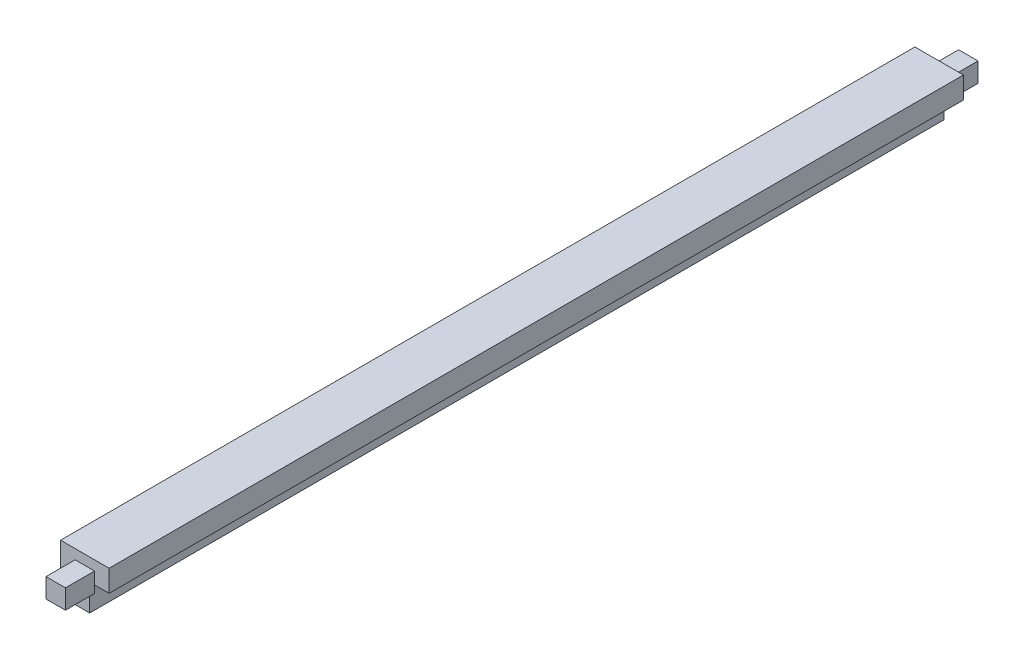
SolidWorks part; units mm, degrees
ref_plane "Front Plane" through (0, 0, 0) normal (0, 0, 1) x (1, 0, 0)
ref_plane "Top Plane" through (0, 0, 0) normal (0, 1, 0) x (1, 0, 0)
ref_plane "Right Plane" through (0, 0, 0) normal (1, 0, 0) x (0, 0, -1)
sketch "Sketch2" plane through (0, 0, 0) normal (0, 1, 0) x (1, 0, 0)
  line L1 (-38.9449, 32.0723) -> (-33.9449, 32.0723)
  line L2 (-38.9449, 32.0723) -> (-38.9449, -55.9277)
  line L3 (-38.9449, -55.9277) -> (-33.9449, -55.9277)
  line L4 (-33.9449, 32.0723) -> (-33.9449, -55.9277)
extrude "Boss-Extrude1" add sketch "Sketch2" along normal blind 5
sketch "Sketch4" plane through (0, 0, -32.0723) normal (0, 0, -1) x (-1, 0, 0)
  line L0 (38.9449, 5) -> (37.4449, 5) construction
  line L1 (37.4449, 5) -> (37.4449, 4) construction
  line L3 (37.4449, 4) -> (35.4449, 4)
  line L4 (37.4449, 4) -> (37.4449, 2)
  line L5 (37.4449, 2) -> (35.4449, 2)
  line L6 (35.4449, 4) -> (35.4449, 2)
sketch "Sketch6" plane through (0, 0, 55.9277) normal (0, 0, 1) x (1, 0, 0)
  line L0 (-38.9449, 5) -> (-37.4449, 5) construction
  line L1 (-37.4449, 5) -> (-37.4449, 4) construction
  line L3 (-37.4449, 4) -> (-35.4449, 4)
  line L4 (-37.4449, 4) -> (-37.4449, 2)
  line L5 (-37.4449, 2) -> (-35.4449, 2)
  line L6 (-35.4449, 4) -> (-35.4449, 2)
extrude "Boss-Extrude4" add sketch "Sketch6" along normal blind 3
extrude "Boss-Extrude3" add sketch "Sketch4" along normal blind 3
sketch "Sketch5" plane through (0, 0, 0) normal (0, -1, 0) x (1, 0, 0)
  line L1 (-33.9449, 55.9277) -> (-35.9449, 55.9277)
  line L2 (-33.9449, 55.9277) -> (-33.9449, -32.0723)
  line L3 (-33.9449, -32.0723) -> (-35.9449, -32.0723)
  line L4 (-35.9449, 55.9277) -> (-35.9449, -32.0723)
extrude "Cut-Extrude2" cut sketch "Sketch5" against normal blind 2.762
